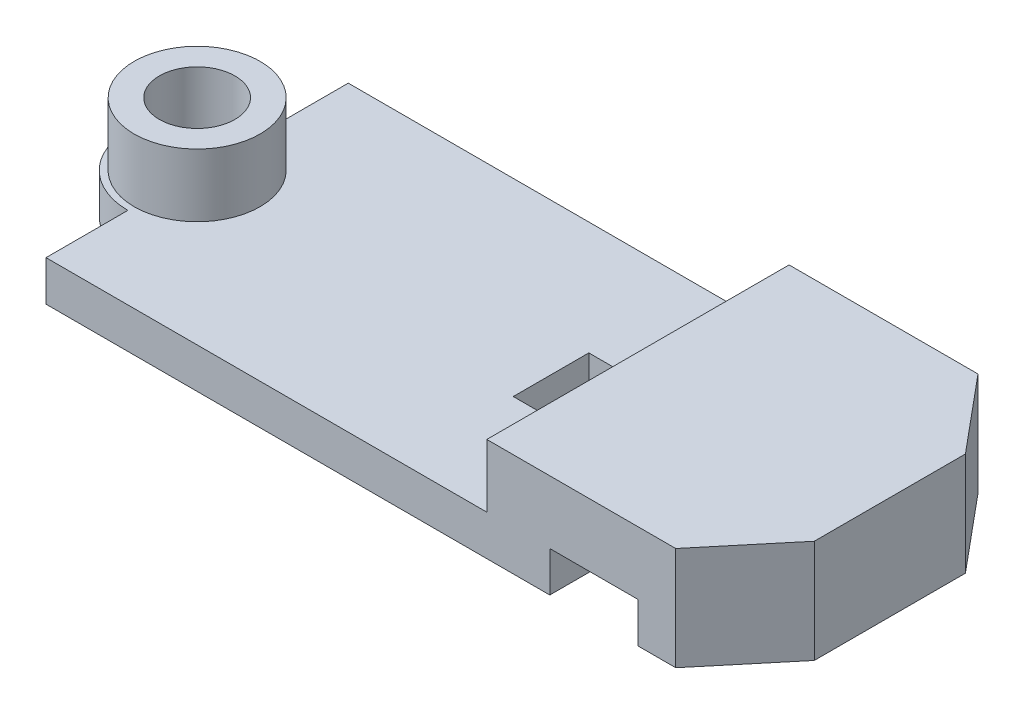
SolidWorks part; units mm, degrees
ref_plane "Alzado" through (0, 0, 0) normal (0, 0, 1) x (1, 0, 0)
ref_plane "Planta" through (0, 0, 0) normal (0, 1, 0) x (1, 0, 0)
ref_plane "Vista lateral" through (0, 0, 0) normal (1, 0, 0) x (0, 0, -1)
sketch "Croquis1" plane through (0, 0, 0) normal (0, 1, 0) x (1, 0, 0)
  line L1 (-87.5, 60) -> (87.5, 60)
  line L2 (-87.5, 60) -> (-87.5, -60)
  line L3 (-87.5, -60) -> (87.5, -60)
  line L4 (87.5, 60) -> (87.5, -60)
  line L5 (-87.5, 60) -> (87.5, -60) construction
  line L6 (-87.5, -60) -> (87.5, 60) construction
  point P0 (0, 0)
  dimension "D1" = 175
  dimension "D2" = 120
extrude "Saliente-Extruir1" add sketch "Croquis1" along normal blind 16
sketch "Croquis2" plane through (0, 16, 0) normal (0, 1, 0) x (1, 0, 0)
  line L0 (0, 0) -> (332.5646, 0) construction
sketch "Croquis6" plane through (0, 0, 0) normal (0, -1, 0) x (1, 0, 0)
  line L0 (87.5, 60) -> (162.5, 60)
  line L1 (87.5, -60) -> (162.5, -60)
  line L2 (187.5, -30) -> (187.5, 30)
  line L4 (187.5, 30) -> (162.5, 60)
  line L5 (162.5, -60) -> (187.5, -30)
  line L6 (0, 0) -> (332.5646, 0) construction
  line L7 (87.5, 60) -> (87.5, -60)
  point P9 (187.5, 0)
  dimension "D1" = 75
  dimension "D2" = 75
  dimension "D3" = 60
  dimension "D4" = 25
  dimension "D5" = 30
extrude "Saliente-Extruir3" add sketch "Croquis6" against normal blind 41 contours L0 L4 L2 L5 L1 L7
sketch "Croquis7" plane through (0, 0, 60) normal (0, 0, 1) x (1, 0, 0)
  line L0 (147.5, 0) -> (112.5, 0)
  line L1 (147.5, 0) -> (147.5, 16)
  line L2 (112.5, 0) -> (112.5, 16)
  line L3 (147.5, 16) -> (112.5, 16)
  line L4 (-87.5, 0) -> (162.5, 0) construction
  line L6 (147.5, 0) -> (112.5, 0)
  dimension "D1" = 40
  dimension "D2" = 16
  dimension "D3" = 35
extrude "Cortar-Extruir1" cut sketch "Croquis7" against normal through all contours L1 L3 L2 L0
sketch "Croquis11" plane through (0, 16, 0) normal (0, 1, 0) x (1, 0, 0)
  line L0 (0, 0) -> (332.5646, 0) construction
  line L1 (53, 15) -> (78, 15)
  line L2 (53, 15) -> (53, -15)
  line L3 (53, -15) -> (78, -15)
  line L4 (78, 15) -> (78, -15)
  line L5 (53, 15) -> (78, -15) construction
  line L6 (53, -15) -> (78, 15) construction
  line L7 (187.5, 30) -> (187.5, -30) construction
  point P0 (65.5, 0)
  dimension "D1" = 25
  dimension "D2" = 30
  dimension "D3" = 122
extrude "Cortar-Extruir2" cut sketch "Croquis11" against normal through all contours L1 L4 L3 L2
sketch "Croquis12" plane through (0, 16, 0) normal (0, 1, 0) x (1, 0, 0)
  line L0 (-87.5, 60) -> (-87.5, -60) construction
  circle A0 centre (-87.5, 0) radius 25
  dimension "D1" = 50
extrude "Saliente-Extruir4" add sketch "Croquis12" along normal blind 25 contours A0
sketch "Croquis14" plane through (0, 0, 0) normal (0, -1, 0) x (1, 0, 0)
  line L0 (-87.5, -25) -> (-87.5, 25) construction
  circle A0 centre (-87.5, 0) radius 27.5
  dimension "D1" = 55
extrude "Saliente-Extruir7" add sketch "Croquis14" against normal blind 16 contours A0
sketch "Croquis15" plane through (0, 0, 0) normal (0, -1, 0) x (-1, 0, 0)
  line L0 (87.5, 27.5) -> (87.5, -27.5) construction
  line L1 (87.5, 25) -> (87.5, -25)
  arc A0 (87.5, -25) -> (87.5, 25) centre (87.5, 0) ccw
  point P5 (87.5, 0)
  dimension "D1" = 50
extrude "Saliente-Extruir8" add sketch "Croquis15" along normal blind 30 contours A0 L1
sketch "Croquis16" plane through (0, 0, 0) normal (0, -1, 0) x (1, 0, 0)
  line L0 (-87.5, -25) -> (-87.5, 25) construction
  line L1 (-87.5, 30) -> (-87.5, -30)
  arc A0 (-87.5, -30) -> (-87.5, 30) centre (-87.5, 0) ccw
  dimension "D1" = 60
extrude "Saliente-Extruir9" add sketch "Croquis16" along normal blind 30
sketch "Croquis17" plane through (0, 41, 0) normal (0, 1, 0) x (1, 0, 0)
  circle A0 centre (-87.5, 0) radius 15
  dimension "D1" = 30
extrude "Cortar-Extruir3" cut sketch "Croquis17" against normal through all
